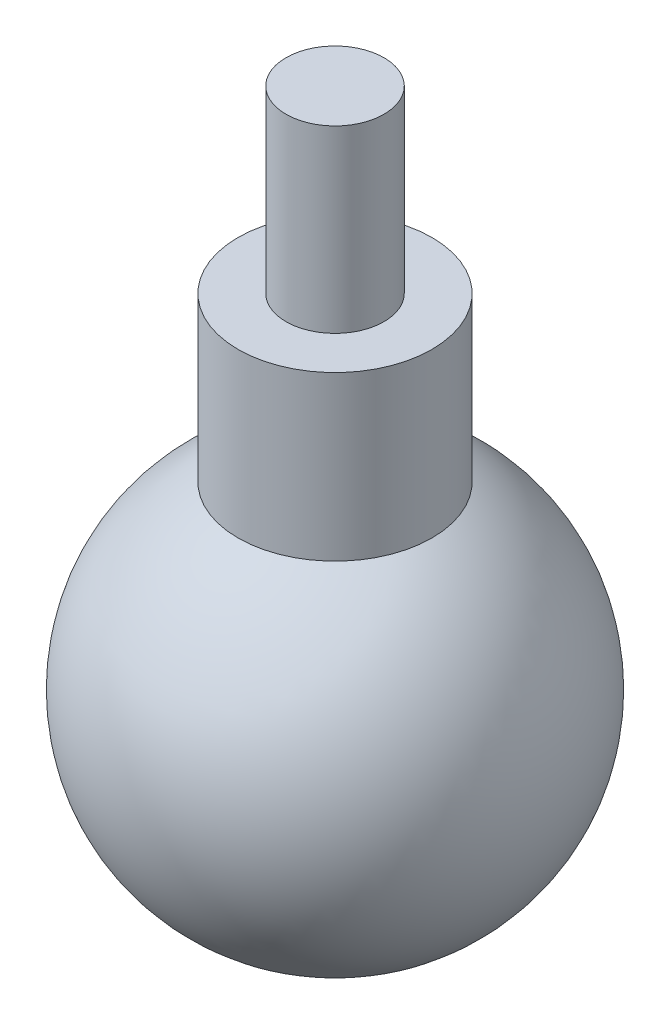
SolidWorks part; units mm, degrees
ref_plane "Plan de face" through (0, 0, 0) normal (0, 0, 1) x (1, 0, 0)
ref_plane "Plan de dessus" through (0, 0, 0) normal (0, 1, 0) x (1, 0, 0)
ref_plane "Plan de droite" through (0, 0, 0) normal (1, 0, 0) x (0, 0, -1)
sketch "Esquisse1" plane through (0, 0, 0) normal (0, 0, 1) x (1, 0, 0)
  line L0 (0, -23.1839) -> (0, 1.8161)
  arc A0 (0, 1.8161) -> (0, -23.1839) centre (0, -10.6839) ccw
  dimension "D2" = 12.5
  dimension "D1" = 25
revolve "Révolution1" add sketch "Esquisse1" angle 360 about L0
sketch "Esquisse4" plane through (0, 0, 0) normal (0, 0, 1) x (1, 0, 0)
  line L1 (15.0983, 0.3161) -> (-16.4826, 0.3161)
  line L2 (15.0983, 0.3161) -> (15.0983, -21.6839)
  line L3 (15.0983, -21.6839) -> (-16.4826, -21.6839)
  line L4 (-16.4826, 0.3161) -> (-16.4826, -21.6839)
  circle A0 centre (0, -10.6839) radius 12.5 construction
  point P0 (0, 1.8161)
  point P1 (0, -23.1839)
  point P4 (0, -10.6839)
  dimension "D1" = 12.5
  dimension "D2" = 12.5
  dimension "D3" = 1.5
  dimension "D4" = 1.5
  dimension "D5" = 11
  dimension "D6" = 11
extrude "Enlèv. mat.-Extru.1" cut sketch "Esquisse4" against normal blind 10 flip side to cut
mirror "Symétrie1" about plane through (0, 0, 0) normal (0, 0, 1) of "Enlèv. mat.-Extru.1"
sketch "Esquisse5" plane through (0, 0.3161, 0) normal (0, 1, 0) x (1, 0, 0)
  circle A0 centre (0, 0) radius 5.9372
extrude "Boss.-Extru.1" add sketch "Esquisse5" along normal blind 10
sketch "Esquisse6" plane through (0, 10.3161, 0) normal (0, 1, 0) x (1, 0, 0)
  circle A0 centre (0, 0) radius 3
  dimension "D1" = 6
extrude "Boss.-Extru.2" add sketch "Esquisse6" along normal blind 11
